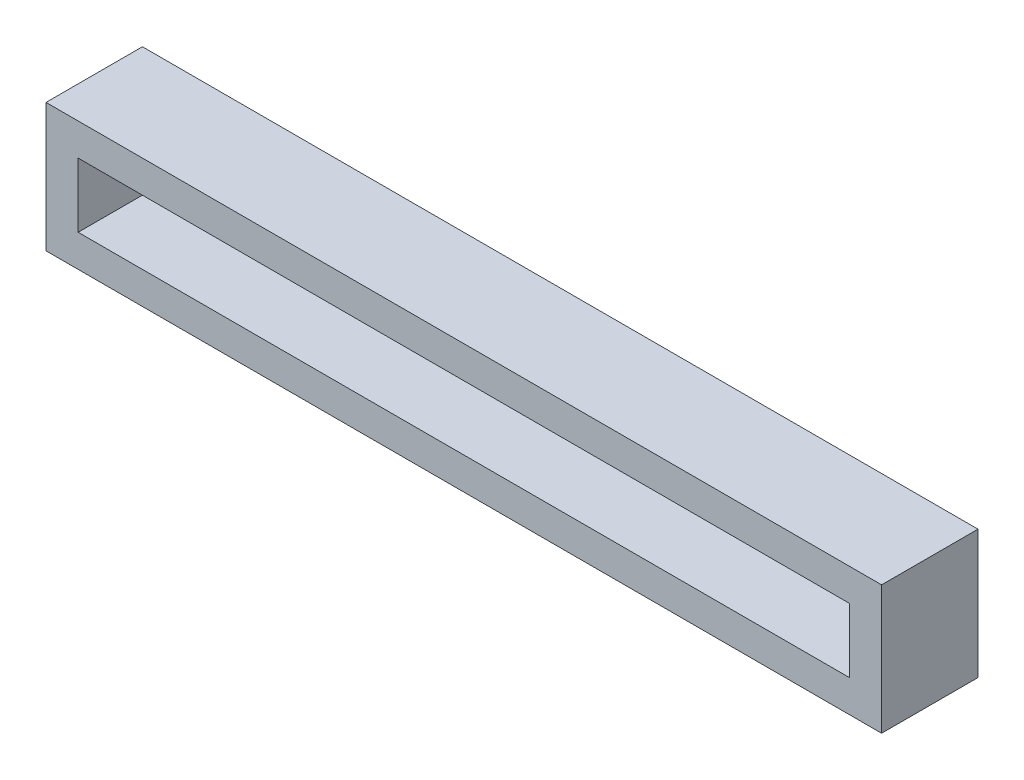
SolidWorks part; units mm, degrees
ref_plane "Alzado" through (0, 0, 0) normal (0, 0, 1) x (1, 0, 0)
ref_plane "Planta" through (0, 0, 0) normal (0, 1, 0) x (1, 0, 0)
ref_plane "Vista lateral" through (0, 0, 0) normal (1, 0, 0) x (0, 0, -1)
sketch "Croquis1" plane through (0, 0, 0) normal (0, 0, 1) x (1, 0, 0)
  line L0 (0, 0) -> (130, 0)
  line L1 (130, 0) -> (130, 20)
  line L2 (130, 20) -> (0, 20)
  line L3 (0, 20) -> (0, 0)
  line L4 (5, 15) -> (5, 5)
  line L5 (5, 5) -> (125, 5)
  line L6 (125, 5) -> (125, 15)
  line L7 (125, 15) -> (5, 15)
  point P7 (65, 15)
  dimension "D1" = 130
  dimension "D2" = 20
  dimension "D3" = 5
  dimension "D4" = 5
  dimension "D5" = 5
  dimension "D6" = 5
extrude "Saliente-Extruir1" add sketch "Croquis1" along normal blind 15
